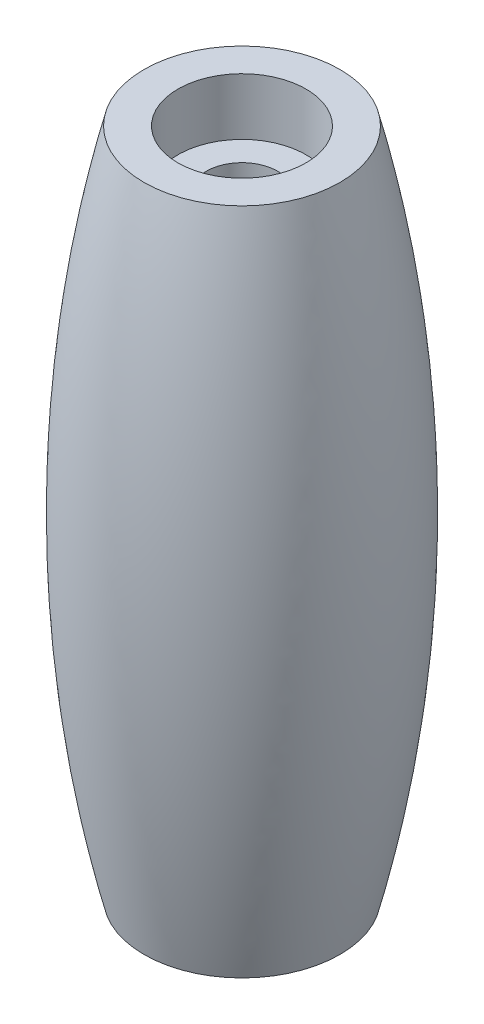
SolidWorks part; units mm, degrees
material "ｼﾘｺﾝ ｺﾞﾑ"
ref_plane "正面" through (0, 0, 0) normal (0, 0, 1) x (1, 0, 0)
ref_plane "平面" through (0, 0, 0) normal (0, 1, 0) x (1, 0, 0)
ref_plane "右側面" through (0, 0, 0) normal (1, 0, 0) x (0, 0, -1)
sketch "ｽｹｯﾁ1" plane through (0, 0, 0) normal (0, 0, 1) x (1, 0, 0)
  line L0 (0, 0) -> (0, 34980.0994) construction
  line L1 (0, 23.5) -> (6.883, 23.5)
  line L2 (0, -23.5) -> (6.883, -23.5)
  line L3 (0, 0) -> (9.725, 0) construction
  line L4 (0, 23.5) -> (0, -23.5)
  ellipse E0 centre (-40.275, 0) end of major axis (-40.275, 70.7107) minor radius 50 (6.883, 23.5) -> (6.883, -23.5) cw
  dimension "D3" = 141.4214
  dimension "D1" = 9.725
  dimension "D2" = 47
  dimension "D4" = 100
revolve "回転1" add sketch "ｽｹｯﾁ1" angle 360 about L0
sketch "ｽｹｯﾁ2" plane through (0, 23.5, 0) normal (0, 1, 0) x (1, 0, 0)
  circle A0 centre (0, 0) radius 4.5
  dimension "D1" = 9
extrude "ｶｯﾄ - 押し出し1" cut sketch "ｽｹｯﾁ2" against normal through all
sketch "ｽｹｯﾁ3" plane through (0, 0, 0) normal (0, 1, 0) x (1, 0, 0)
  circle A0 centre (0, 0) radius 4.5 construction
  circle A1 centre (0, 0) radius 4.5
  circle A2 centre (0, 0) radius 2.5
  dimension "D1" = 5
extrude "ﾎﾞｽ - 押し出し1" add sketch "ｽｹｯﾁ3" along normal blind 19.5 and the other way blind 19.5
